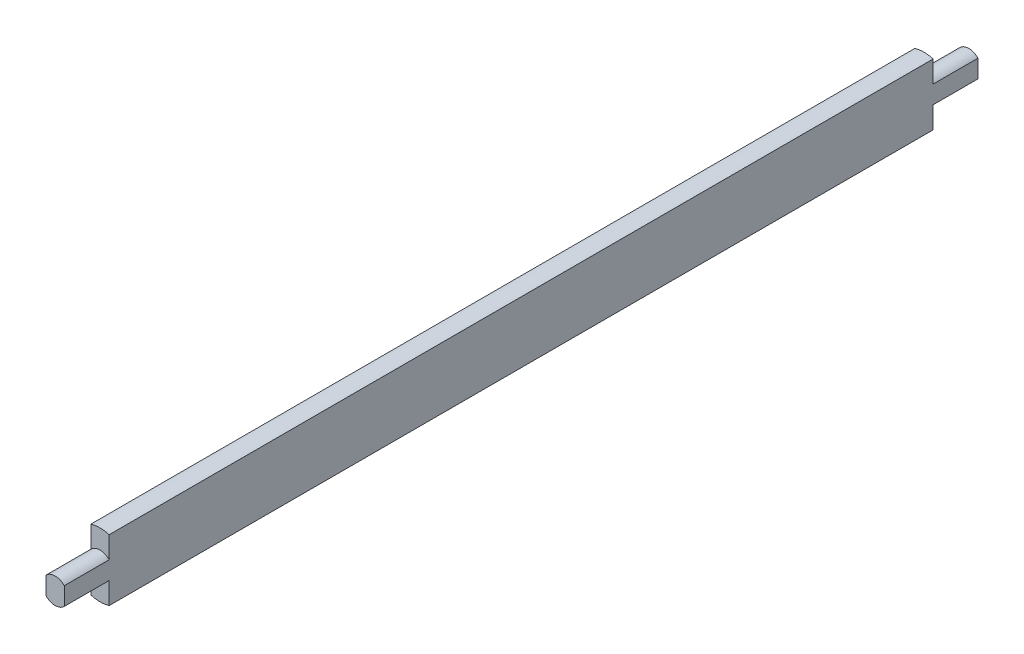
SolidWorks part; units mm, degrees
ref_plane "Ebene vorne" through (0, 0, 0) normal (0, 0, 1) x (1, 0, 0)
ref_plane "Ebene oben" through (0, 0, 0) normal (0, 1, 0) x (1, 0, 0)
ref_plane "Ebene rechts" through (0, 0, 0) normal (1, 0, 0) x (0, 0, -1)
sketch "Skizze1" plane through (0, 0, 0) normal (0, 0, 1) x (1, 0, 0)
  circle A0 centre (0, 0) radius 3.5
  dimension "D1" = 7
extrude "Aufsatz-Linear austragen1" add sketch "Skizze1" along normal blind 90
sketch "Skizze3" plane through (0, 0, 90) normal (0, 0, 1) x (1, 0, 0)
  circle A0 centre (0, 0) radius 1.4
  dimension "D1" = 2.8
sketch "Skizze4" plane through (0, 0, 0) normal (0, 0, -1) x (-1, 0, 0)
  circle A0 centre (0, 0) radius 1.4
  dimension "D1" = 2.8
extrude "Aufsatz-Linear austragen2" add sketch "Skizze3" along normal blind 4.9 contours A0
extrude "Aufsatz-Linear austragen3" add sketch "Skizze4" along normal blind 4.9
sketch "Skizze5" plane through (0, 0, 90) normal (0, 0, 1) x (1, 0, 0)
  line L0 (0, -3.5) -> (0, 3.5) construction
  line L2 (-1, 3.8684) -> (1, 3.8684)
  line L3 (-1, 3.8684) -> (-1, -4.1355)
  line L4 (-1, -4.1355) -> (1, -4.1355)
  line L5 (1, 3.8684) -> (1, -4.1355)
  circle A0 centre (0, 0) radius 3.5 construction
  dimension "D1" = 1
  dimension "D2" = 1
sketch "Skizze11" plane through (0, 0, 90) normal (0, 0, 1) x (1, 0, 0)
  line L1 (1, -4.1355) -> (5.1929, -4.1355)
  line L2 (1, -4.1355) -> (1, 3.8684)
  line L3 (1, 3.8684) -> (5.1929, 3.8684)
  line L4 (5.1929, -4.1355) -> (5.1929, 3.8684)
extrude "Schnitt-Linear austragen7" cut sketch "Skizze11" against normal through all and the other way through all
sketch "Skizze12" plane through (0, 0, 90) normal (0, 0, 1) x (1, 0, 0)
  line L1 (-1, -4.1355) -> (-4.3598, -4.1355)
  line L2 (-1, -4.1355) -> (-1, 3.8593)
  line L3 (-1, 3.8593) -> (-4.3598, 3.8593)
  line L4 (-4.3598, -4.1355) -> (-4.3598, 3.8593)
extrude "Schnitt-Linear austragen8" cut sketch "Skizze12" against normal through all and the other way through all
